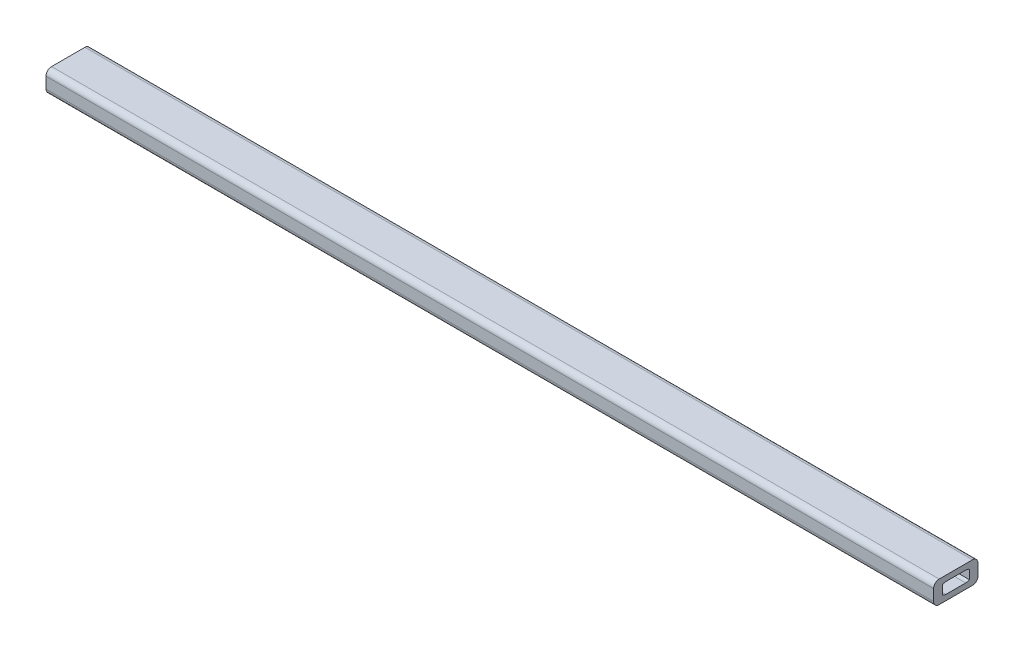
SolidWorks part; units mm, degrees
ref_plane "Front Plane" through (0, 0, 0) normal (0, 0, 1) x (1, 0, 0)
ref_plane "Top Plane" through (0, 0, 0) normal (0, 1, 0) x (1, 0, 0)
ref_plane "Right Plane" through (0, 0, 0) normal (1, 0, 0) x (0, 0, -1)
sketch "Sketch1" plane through (0, 0, 0) normal (1, 0, 0) x (0, 0, -1)
  line L0 (0, 29.6522) -> (0, -37.3043) construction
  line L1 (12.1488, 4.0496) -> (12.1488, -4.0496)
  line L2 (-8.8703, 5) -> (8.8703, 5)
  line L4 (-8.8703, -5) -> (8.8703, -5)
  line L6 (-15, 5) -> (15, -5) construction
  line L7 (-15, -5) -> (15, 5) construction
  line L8 (-15, 10) -> (15, 10)
  line L9 (-20, 5) -> (-20, -5)
  line L10 (-15, -10) -> (15, -10)
  line L11 (20, 5) -> (20, -5)
  line L12 (-20, 10) -> (20, -10) construction
  line L13 (-20, -10) -> (20, 10) construction
  line L14 (-12.1488, 4.0496) -> (-12.1488, -4.0496)
  arc A0 (-20, 5) -> (-15, 10) centre (-15, 5) cw
  arc A1 (20, 5) -> (15, 10) centre (15, 5) ccw
  arc A2 (15, -10) -> (20, -5) centre (15, -5) ccw
  arc A3 (-20, -5) -> (-15, -10) centre (-15, -5) ccw
  arc A5 (12.1488, 4.0496) -> (8.8703, 5) centre (8.8703, -1.1297) ccw
  arc A7 (-12.1488, -4.0496) -> (-8.8703, -5) centre (-8.8703, 1.1297) ccw
  arc A8 (-12.1488, 4.0496) -> (-8.8703, 5) centre (-8.8703, -1.1297) cw
  arc A9 (12.1488, -4.0496) -> (8.8703, -5) centre (8.8703, 1.1297) cw
  point P3 (0, 0)
  point P8 (0, 0)
  dimension "D5" = 5
  dimension "D6" = 5
  dimension "D1" = 40
  dimension "D2" = 20
  dimension "D3" = 10
  dimension "D4" = 30
extrude "Boss-Extrude1" add sketch "Sketch1" along normal mid plane 800
